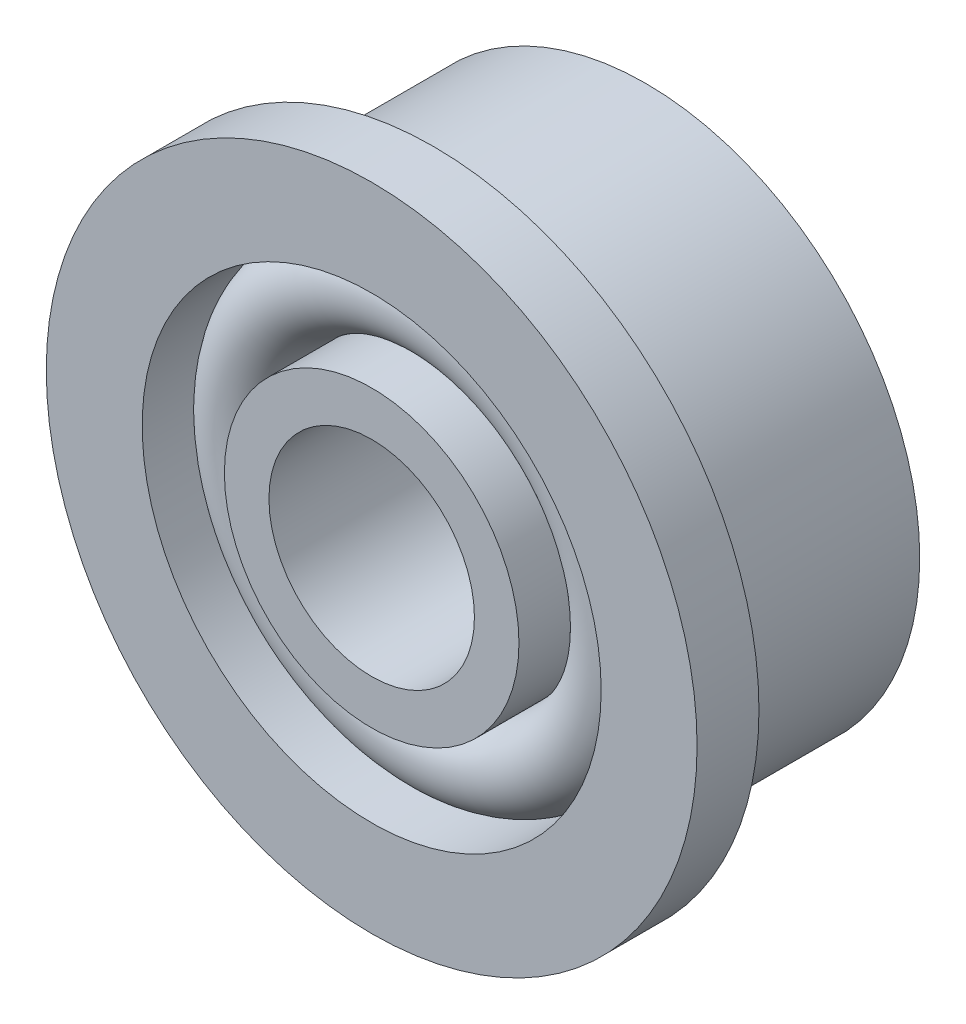
SolidWorks part; units mm, degrees
ref_plane "Plan de face" through (0, 0, 0) normal (0, 0, 1) x (1, 0, 0)
ref_plane "Plan de dessus" through (0, 0, 0) normal (0, 1, 0) x (1, 0, 0)
ref_plane "Plan de droite" through (0, 0, 0) normal (1, 0, 0) x (0, 0, -1)
sketch "Esquisse1" plane through (0, 0, 0) normal (1, 0, 0) x (0, 0, -1)
  line L0 (0, 1.5) -> (4, 1.5)
  line L1 (4, 1.5) -> (4, 2.15)
  line L2 (4, 2.15) -> (3, 2.15)
  line L3 (3, 3.35) -> (4, 3.35)
  line L4 (4, 3.35) -> (4, 4)
  line L5 (4, 4) -> (0.9033, 4)
  line L6 (0.9033, 4) -> (0.9033, 4.75)
  line L7 (0.9033, 4.75) -> (0, 4.75)
  line L8 (0, 4.75) -> (0, 3.35)
  line L9 (0, 3.35) -> (1, 3.35)
  line L10 (1, 2.15) -> (0, 2.15)
  line L11 (0, 2.15) -> (0, 1.5)
  line L12 (0, 0) -> (8.1757, 0) construction
  line L13 (1, 2.75) -> (3, 2.75) construction
  line L14 (1, 3.35) -> (3, 3.35) construction
  arc A0 (3, 2.15) -> (3, 3.35) centre (3, 2.75) ccw
  arc A1 (1, 3.35) -> (1, 2.15) centre (1, 2.75) ccw
  dimension "D1" = 4
  dimension "D2" = 4.75
  dimension "D3" = 4
  dimension "D4" = 1.5
  dimension "D5" = 0.9033
  dimension "D6" = 1
  dimension "D7" = 1
  dimension "D8" = 0.65
  dimension "D9" = 0.65
revolve "Révolution1" add sketch "Esquisse1" angle 360 about L12
